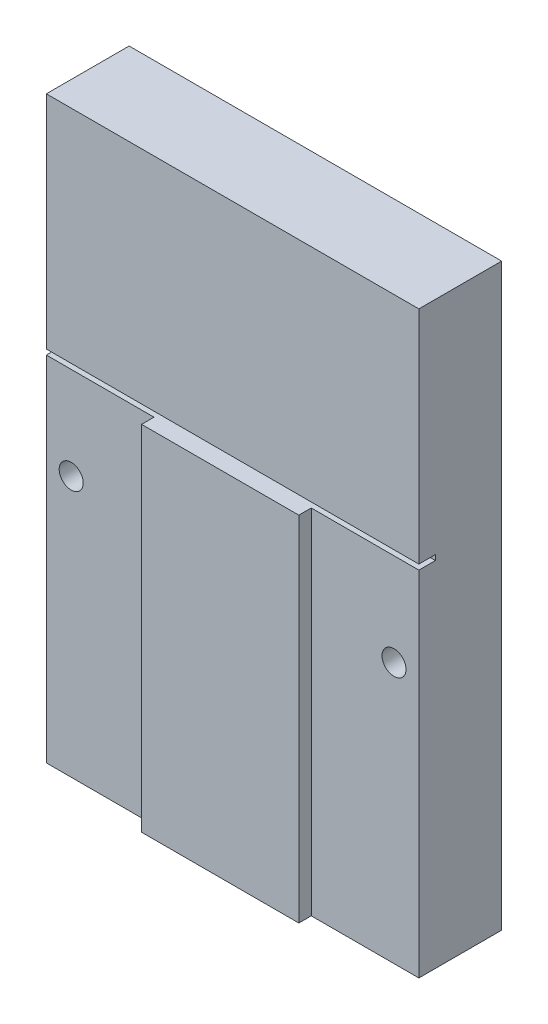
SolidWorks part; units mm, degrees
ref_plane "Front Plane" through (0, 0, 0) normal (0, 0, 1) x (1, 0, 0)
ref_plane "Top Plane" through (0, 0, 0) normal (0, 1, 0) x (1, 0, 0)
ref_plane "Right Plane" through (0, 0, 0) normal (1, 0, 0) x (0, 0, -1)
sketch "Sketch2" plane through (0, 0, 0) normal (0, 1, 0) x (1, 0, 0)
  line L1 (22.5, 5) -> (-22.5, 5)
  line L2 (22.5, 5) -> (22.5, -5)
  line L3 (22.5, -5) -> (-22.5, -5)
  line L4 (-22.5, 5) -> (-22.5, -5)
  line L5 (22.5, 5) -> (-22.5, -5) construction
  line L6 (22.5, -5) -> (-22.5, 5) construction
  point P0 (0, 0)
  dimension "D1" = 10
  dimension "D2" = 45
extrude "Boss-Extrude1" add sketch "Sketch2" along normal blind 40
sketch "Sketch3" plane through (0, 0, -5) normal (0, 0, -1) x (-1, 0, 0)
  line L0 (0, 0) -> (0, 40) construction
  line L1 (-22.5, 40) -> (22.5, 40) construction
  line L3 (22.5, 40) -> (22.5, 0) construction
  line L4 (-22.5, 40) -> (-22.5, 0) construction
  line L5 (-22.5, 0) -> (22.5, 0) construction
  line L6 (-22.5, 11.5) -> (22.5, 11.5) construction
  circle A0 centre (19.5, 2.25) radius 1.45
  circle A3 centre (-19.5, 2.25) radius 1.45
  circle A4 centre (-19.5, 20.75) radius 1.45
  circle A5 centre (19.5, 20.75) radius 1.45
  dimension "D3" = 2.9
  dimension "D4" = 3
  dimension "D1" = 3
  dimension "D2" = 2.25
sketch "Sketch4" plane through (0, 40, 0) normal (0, 1, 0) x (1, 0, 0)
  line L1 (-22.5, 5) -> (22.5, 5)
  line L2 (-22.5, 5) -> (-22.5, -5)
  line L3 (-22.5, -5) -> (22.5, -5)
  line L4 (22.5, 5) -> (22.5, -5)
extrude "Boss-Extrude2" add sketch "Sketch4" along normal blind 10
sketch "Sketch6" plane through (0, 0, -5) normal (0, 0, -1) x (-1, 0, 0)
  line L2 (-22.5, 23) -> (22.7712, 23) construction
  circle A1 centre (-19.5, 20.75) radius 1.45 construction
  dimension "D1" = 2.25
sketch "Sketch8" plane through (0, 0, 0) normal (0, -1, 0) x (1, 0, 0)
  line L1 (-22.5, 5) -> (22.5, 5)
  line L2 (-22.5, 5) -> (-22.5, -5)
  line L3 (-22.5, -5) -> (22.5, -5)
  line L4 (22.5, 5) -> (22.5, -5)
extrude "Boss-Extrude3" add sketch "Sketch8" along normal blind 20
sketch "Sketch9" plane through (0, 0, 5) normal (0, 0, 1) x (1, 0, 0)
  line L0 (22.5, 11.5) -> (-22.5, 11.5) construction
  line L1 (-22.5, 50) -> (-22.5, -20) construction
  line L2 (22.5, 50) -> (22.5, -20) construction
  circle A0 centre (19.5, 20.75) radius 1.45 construction
  circle A1 centre (19.5, 2.25) radius 1.45 construction
  circle A2 centre (19.5, 11.5) radius 1.45
  circle A3 centre (-19.5, 11.5) radius 1.45
  dimension "D1" = 18.5
  dimension "D2" = 3
  dimension "D3" = 3
  dimension "D4" = 3
extrude "Cut-Extrude2" cut sketch "Sketch9" against normal blind 20
sketch "Sketch10" plane through (0, 0, 5) normal (0, 0, 1) x (1, 0, 0)
  line L1 (-22.5, 50) -> (-22.5, -20) construction
  line L2 (-22.5, 23.2975) -> (22.5, 23.2975)
  line L3 (-22.5, 23.2975) -> (-22.5, 22.6713)
  line L4 (-22.5, 22.6713) -> (22.5, 22.6713)
  line L5 (22.5, 23.2975) -> (22.5, 22.6713)
  line L6 (22.5, 50) -> (22.5, -20) construction
extrude "Cut-Extrude3" cut sketch "Sketch10" against normal blind 2
sketch "Sketch11" plane through (0, 0, 5) normal (0, 0, 1) x (1, 0, 0)
  line L0 (-22.5, 22.6713) -> (22.5, 22.6713) construction
  line L1 (-9.5, 22.6713) -> (9.5, 22.6713)
  line L2 (-9.5, 22.6713) -> (-9.5, -20)
  line L3 (-9.5, -20) -> (9.5, -20)
  line L4 (9.5, 22.6713) -> (9.5, -20)
  line L5 (22.5, -20) -> (-22.5, -20) construction
  line L6 (22.5, 22.6713) -> (22.5, -20) construction
  line L8 (-22.5, 22.6713) -> (-22.5, -20) construction
  dimension "D1" = 19
  dimension "D2" = 13
  dimension "D3" = 13
extrude "Boss-Extrude4" add sketch "Sketch11" along normal blind 1.5
